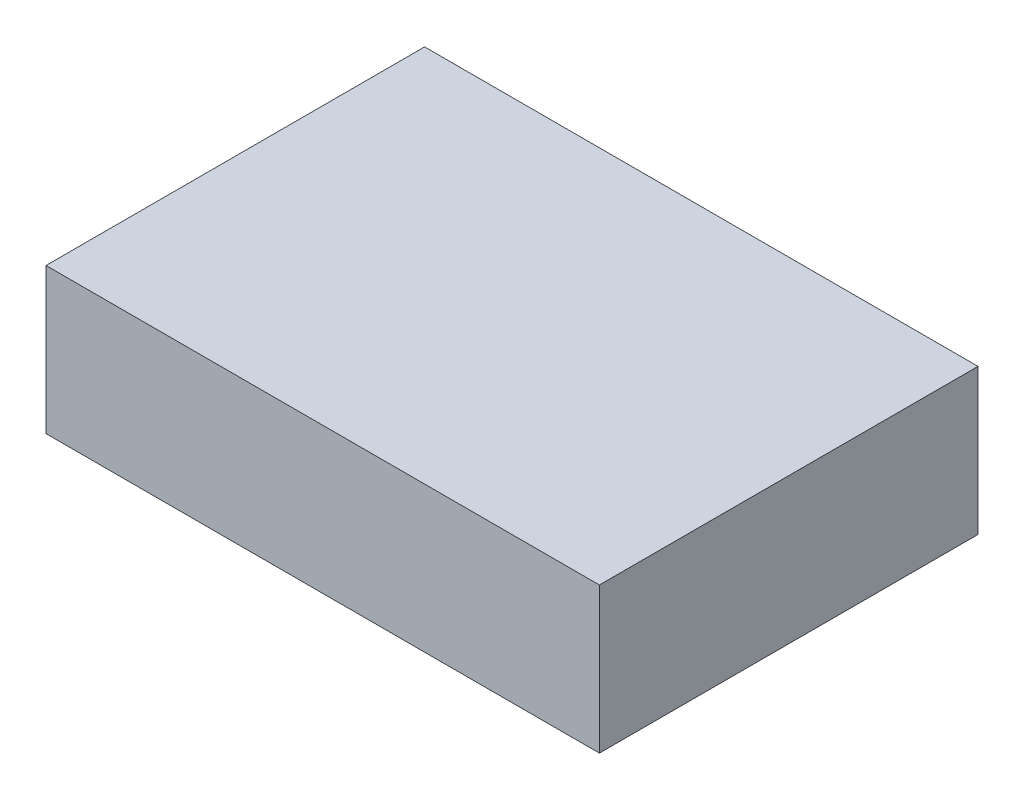
SolidWorks part; units mm, degrees
ref_plane "Front Plane" through (0, 0, 0) normal (0, 0, 1) x (1, 0, 0)
ref_plane "Top Plane" through (0, 0, 0) normal (0, 1, 0) x (1, 0, 0)
ref_plane "Right Plane" through (0, 0, 0) normal (1, 0, 0) x (0, 0, -1)
sketch "Sketch1" plane through (0, 0, 0) normal (0, 1, 0) x (1, 0, 0)
  line L1 (-30.1625, -20.6375) -> (30.1625, -20.6375)
  line L2 (-30.1625, -20.6375) -> (-30.1625, 20.6375)
  line L3 (-30.1625, 20.6375) -> (30.1625, 20.6375)
  line L4 (30.1625, -20.6375) -> (30.1625, 20.6375)
  line L5 (-30.1625, -20.6375) -> (30.1625, 20.6375) construction
  line L6 (-30.1625, 20.6375) -> (30.1625, -20.6375) construction
  point P0 (0, 0)
  dimension "D1" = 60.325
  dimension "D2" = 41.275
extrude "Boss-Extrude1" add sketch "Sketch1" along normal blind 15.875
